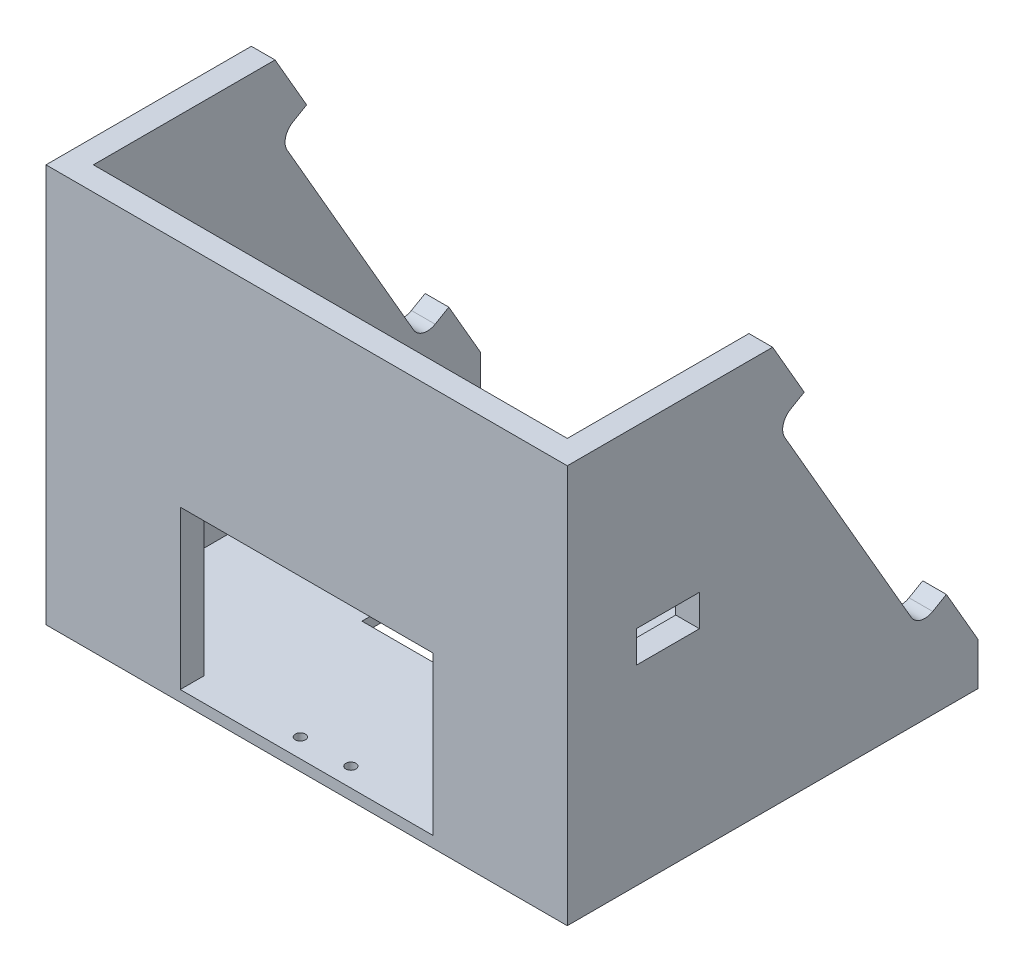
SolidWorks part; units mm, degrees
ref_plane "Front Plane" through (0, 0, 0) normal (0, 0, 1) x (1, 0, 0)
ref_plane "Top Plane" through (0, 0, 0) normal (0, 1, 0) x (1, 0, 0)
ref_plane "Right Plane" through (0, 0, 0) normal (1, 0, 0) x (0, 0, -1)
sketch "Sketch2" plane through (0, 0, 0) normal (1, 0, 0) x (0, 0, -1)
  line L1 (0, 112.5833) -> (65, 0)
  line L2 (65, 0) -> (0, 0)
  line L4 (0, 112.5833) -> (-65, 112.5833)
  line L6 (0, 0) -> (-65, 0)
  line L7 (-65, 112.5833) -> (-65, 0)
  dimension "D1" = 60
  dimension "D2" = 130
  dimension "D3" = 65
extrude "Boss-Extrude1" add sketch "Sketch2" along normal mid plane 165
sketch "Sketch4" plane through (0, 28.1458, -48.75) normal (0, 0.5, -0.866) x (-1, 0, 0)
  line L0 (-82.5, -32.5) -> (-82.5, 97.5) construction
  line L1 (-82.5, 77.5) -> (82.5, 77.5)
  line L2 (-82.5, 77.5) -> (-82.5, -12.5)
  line L3 (-82.5, -12.5) -> (82.5, -12.5)
  line L4 (82.5, 77.5) -> (82.5, -12.5)
  line L5 (82.5, -32.5) -> (82.5, 97.5) construction
  line L6 (-82.5, 32.5) -> (82.5, 32.5) construction
  dimension "D1" = 90
extrude "Cut-Extrude1" cut sketch "Sketch4" against normal blind 10
sketch "Sketch6" plane through (0, 112.5833, 0) normal (0, 1, 0) x (1, 0, 0)
  line L1 (-75, -57.5) -> (75, -57.5)
  line L2 (-75, -57.5) -> (-75, 65)
  line L3 (-75, 65) -> (75, 65)
  line L4 (75, -57.5) -> (75, 65)
  line L5 (82.5, 65) -> (-82.5, 65) construction
  line L6 (82.5, -65) -> (-82.5, -65) construction
  line L7 (-82.5, 65) -> (-82.5, 55) construction
  point P8 (0, 65)
  dimension "D1" = 7.5
  dimension "D2" = 7.5
extrude "Cut-Extrude2" cut sketch "Sketch6" against normal through all
sketch "Sketch7" plane through (0, 0, 65) normal (0, 0, 1) x (1, 0, 0)
  line L0 (82.5, 0) -> (-82.5, 0) construction
  line L1 (-40, 0) -> (40, 0)
  line L2 (-40, 0) -> (-40, 40)
  line L3 (-40, 40) -> (40, 40)
  line L4 (40, 0) -> (40, 40)
  point P6 (0, 40)
  dimension "D1" = 40
  dimension "D2" = 80
extrude "Cut-Extrude3" cut sketch "Sketch7" against normal blind 60
sketch "Sketch8" plane through (0, 0, 57.5) normal (0, 0, -1) x (-1, 0, 0)
  line L0 (-75, 0) -> (-75, 112.5833) construction
  line L1 (-75, 40) -> (75, 40)
  line L2 (-75, 40) -> (-75, 42)
  line L3 (-75, 42) -> (75, 42)
  line L4 (75, 40) -> (75, 42)
  line L5 (75, 0) -> (75, 112.5833) construction
  line L8 (-40, 40) -> (40, 40) construction
  dimension "D1" = 2
extrude "Boss-Extrude2" add sketch "Sketch8" along normal up to vertex (57.5 mm away) up to point (-75, 112.5833, 0)
sketch "Sketch9" plane through (-82.5, 0, 0) normal (-1, 0, 0) x (0, 0, 1)
  line L0 (0, 42) -> (57.5, 42) construction
  line L1 (23.1701, 57) -> (43.1701, 57)
  line L2 (23.1701, 57) -> (23.1701, 47)
  line L3 (23.1701, 47) -> (43.1701, 47)
  line L4 (43.1701, 57) -> (43.1701, 47)
  line L5 (0, 42) -> (57.5, 42) construction
  dimension "D1" = 5
  dimension "D2" = 20
  dimension "D3" = 10
extrude "Cut-Extrude4" cut sketch "Sketch9" against normal through all
sketch "Sketch10" plane through (0, 28.1458, -48.75) normal (0, 0.5, -0.866) x (-1, 0, 0)
  circle A0 centre (-78.5, 89.2555) radius 2
  circle A1 centre (78.5, 89.2555) radius 2
  circle A2 centre (78.5, -25.2445) radius 2
  circle A3 centre (-78.5, -25.7445) radius 2
  dimension "D1" = 4
extrude "Cut-Extrude5" cut sketch "Sketch10" against normal blind 6
chamfer "Chamfer1" distance 5 angle 45 4 edges at (-75, 40, 28.75) (-57.5, 40, 57.5) (57.5, 40, 57.5) (75, 40, 28.75)
fillet "Fillet1" radius 5 4 edges at (-78.75, 12.3205, -46.3397) (78.75, 12.3205, -46.3397) (78.75, 90.2628, -1.3397) (-78.75, 90.2628, -1.3397)
sketch "Sketch12" plane through (0, 0, 0) normal (0, -1, 0) x (1, 0, 0)
  line L0 (82.5, 65) -> (40, 65) construction
  line L1 (40, 65) -> (40, 57.5) construction
  line L2 (40, 57.5) -> (75, 57.5) construction
  line L3 (75, 57.5) -> (75, -65) construction
  line L4 (75, -65) -> (82.5, -65) construction
  line L5 (82.5, -65) -> (82.5, 65) construction
  line L6 (-75, 57.5) -> (-40, 57.5) construction
  line L7 (-40, 57.5) -> (-40, 65) construction
  line L8 (-40, 65) -> (-82.5, 65) construction
  line L9 (-82.5, 65) -> (-82.5, -65) construction
  line L10 (-82.5, -65) -> (-75, -65) construction
  line L11 (-75, -65) -> (-75, 57.5) construction
  line L12 (82.5, 65) -> (40, 65)
  line L13 (40, 65) -> (40, 57.5)
  line L14 (40, 57.5) -> (75, 57.5)
  line L15 (75, 57.5) -> (75, -65)
  line L16 (75, -65) -> (82.5, -65)
  line L17 (82.5, -65) -> (82.5, 65)
  line L18 (-75, 57.5) -> (-40, 57.5)
  line L19 (-40, 57.5) -> (-40, 65)
  line L20 (-40, 65) -> (-82.5, 65)
  line L21 (-82.5, 65) -> (-82.5, -65)
  line L22 (-82.5, -65) -> (-75, -65)
  line L23 (-75, -65) -> (-75, 57.5)
extrude "Boss-Extrude3" add sketch "Sketch12" along normal blind 10
sketch "Sketch17" plane through (0, -10, 0) normal (0, -1, 0) x (1, 0, 0)
  line L1 (-82.5, 65) -> (82.5, 65)
  line L2 (-82.5, 65) -> (-82.5, -65)
  line L3 (-82.5, -65) -> (82.5, -65)
  line L4 (82.5, 65) -> (82.5, -65)
extrude "Boss-Extrude4" add sketch "Sketch17" along normal blind 3.5
sketch "Sketch16" plane through (0, -13.5, 0) normal (0, -1, 0) x (1, 0, 0)
  line L9 (0, 0) -> (0, 90.9907) construction
  line L10 (70, 0) -> (-70, 0) construction
  line L12 (-65, -60) -> (65, -60) construction
  line L13 (-65, -60) -> (-65, 60) construction
  line L14 (-65, 60) -> (65, 60) construction
  line L15 (65, -60) -> (65, 60) construction
  line L16 (0, 60) -> (0, -60) construction
  line L17 (-65, 0) -> (65, 0) construction
  circle A8 centre (-65, 60) radius 2
  circle A9 centre (65, 60) radius 2
  circle A10 centre (65, -60) radius 2
  circle A11 centre (-65, -60) radius 2
  dimension "D1" = 130
  dimension "D2" = 120
  dimension "D3" = 4
extrude "Cut-Extrude6" cut sketch "Sketch16" against normal blind 4
sketch "Sketch19" plane through (0, -13.5, 0) normal (0, -1, 0) x (1, 0, 0)
  line L0 (-8, 59) -> (8, 59) construction
  line L1 (-30, 17.5) -> (30, 17.5)
  line L2 (-30, 17.5) -> (-30, -17.5)
  line L3 (-30, -17.5) -> (30, -17.5)
  line L4 (30, 17.5) -> (30, -17.5)
  line L5 (0, -17.5) -> (0, 17.5) construction
  line L6 (-30, 0) -> (30, 0) construction
  line L7 (82.5, 65) -> (-82.5, 65) construction
  circle A0 centre (-8, 59) radius 1.6
  circle A1 centre (8, 59) radius 1.6
  point P0 (0, 0)
  point P7 (0, 59)
  dimension "D5" = 3.2
  dimension "D1" = 35
  dimension "D2" = 60
  dimension "D3" = 16
  dimension "D4" = 6
extrude "Cut-Extrude7" cut sketch "Sketch19" against normal blind 10
